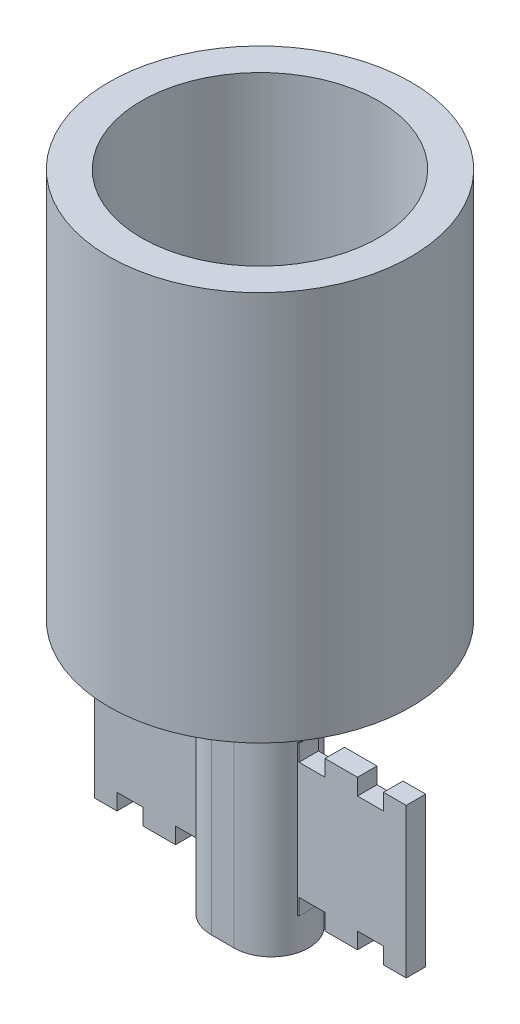
SolidWorks part; units mm, degrees
material "ABS"
ref_plane "Front Plane" through (0, 0, 0) normal (0, 0, 1) x (1, 0, 0)
ref_plane "Top Plane" through (0, 0, 0) normal (0, 1, 0) x (1, 0, 0)
ref_plane "Right Plane" through (0, 0, 0) normal (1, 0, 0) x (0, 0, -1)
sketch "Sketch1" plane through (0, 0, 0) normal (0, 1, 0) x (1, 0, 0)
  circle A0 centre (0, 0) radius 4.65
  dimension "D1" = 9.3
extrude "Boss-Extrude1" add sketch "Sketch1" along normal blind 1
sketch "Sketch2" plane through (0, 1, 0) normal (0, 1, 0) x (1, 0, 0)
  circle A0 centre (0, 0) radius 4.65 construction
  circle A1 centre (0, 0) radius 4.65
  circle A2 centre (0, 0) radius 3.65
  dimension "D1" = 1
extrude "Boss-Extrude2" add sketch "Sketch2" along normal blind 11
sketch "Sketch3" plane through (0, 0, 0) normal (0, -1, 0) x (1, 0, 0)
  line L0 (0.35, 0) -> (-0.35, 0) construction
  line L1 (0.35, -1.15) -> (-0.35, -1.15)
  line L2 (0.35, 1.15) -> (-0.35, 1.15)
  arc A0 (0.35, -1.15) -> (0.35, 1.15) centre (0.35, 0) ccw
  arc A1 (-0.35, 1.15) -> (-0.35, -1.15) centre (-0.35, 0) ccw
  point P2 (0, 0)
  point P8 (-1.5, 0)
  point P9 (1.5, 0)
  dimension "D1" = 1.15
  dimension "D2" = 3
extrude "Boss-Extrude3" add sketch "Sketch3" along normal blind 8
sketch "Sketch4" plane through (0, 0, 0) normal (0, 0, 1) x (1, 0, 0)
  line L0 (0.35, -8) -> (1.5, -8) construction
  line L1 (4.8, -2.4) -> (-4.8, -2.4)
  line L2 (4.8, -2.4) -> (4.8, -7)
  line L3 (4.8, -7) -> (-4.8, -7)
  line L4 (-4.8, -2.4) -> (-4.8, -7)
  line L5 (4.8, -2.4) -> (-4.8, -7) construction
  line L6 (4.8, -7) -> (-4.8, -2.4) construction
  point P0 (0, -4.7)
  dimension "D1" = 1
  dimension "D2" = 4.6
  dimension "D3" = 9.6
extrude "Boss-Extrude4" add sketch "Sketch4" along normal mid plane 0.6
sketch "Sketch5" plane through (0, 0, -0.3) normal (0, 0, -1) x (-1, 0, 0)
  line L0 (-4.8, -2.4) -> (-1.4602, -2.4) construction
  line L1 (-1.5, -2.4) -> (-2.3, -2.4)
  line L2 (-1.5, -2.4) -> (-1.5, -2.9)
  line L3 (-1.5, -2.9) -> (-2.3, -2.9)
  line L4 (-2.3, -2.4) -> (-2.3, -2.9)
  line L5 (-3.3, -2.4) -> (-4.1, -2.4)
  line L6 (-3.3, -2.4) -> (-3.3, -2.9)
  line L7 (-3.3, -2.9) -> (-4.1, -2.9)
  line L8 (-4.1, -2.4) -> (-4.1, -2.9)
  line L9 (0, 5.115) -> (0, -5.115) construction
  line L10 (4.1, -2.4) -> (4.1, -2.9)
  line L11 (3.3, -2.9) -> (4.1, -2.9)
  line L12 (3.3, -2.4) -> (3.3, -2.9)
  line L13 (3.3, -2.4) -> (4.1, -2.4)
  line L14 (2.3, -2.4) -> (2.3, -2.9)
  line L15 (1.5, -2.9) -> (2.3, -2.9)
  line L16 (1.5, -2.4) -> (1.5, -2.9)
  line L17 (1.5, -2.4) -> (2.3, -2.4)
  line L18 (-4.8, -4.7) -> (-1.4602, -4.7) construction
  line L19 (-4.8, -7) -> (-4.8, -2.4) construction
  line L20 (-1.4602, -2.4) -> (-1.4602, -7) construction
  line L21 (1.5, -7) -> (2.3, -7)
  line L22 (1.5, -7) -> (1.5, -6.5)
  line L23 (1.5, -6.5) -> (2.3, -6.5)
  line L24 (2.3, -7) -> (2.3, -6.5)
  line L25 (3.3, -7) -> (4.1, -7)
  line L26 (3.3, -7) -> (3.3, -6.5)
  line L27 (3.3, -6.5) -> (4.1, -6.5)
  line L28 (4.1, -7) -> (4.1, -6.5)
  line L29 (-4.1, -7) -> (-4.1, -6.5)
  line L30 (-3.3, -6.5) -> (-4.1, -6.5)
  line L31 (-3.3, -7) -> (-3.3, -6.5)
  line L32 (-3.3, -7) -> (-4.1, -7)
  line L33 (-2.3, -7) -> (-2.3, -6.5)
  line L34 (-1.5, -6.5) -> (-2.3, -6.5)
  line L35 (-1.5, -7) -> (-1.5, -6.5)
  line L36 (-1.5, -7) -> (-2.3, -7)
  dimension "D1" = 0.8
  dimension "D2" = 0.5
  dimension "D3" = 1
extrude "Cut-Extrude1" cut sketch "Sketch5" against normal through all
sketch "Sketch6" plane through (0, 0, 0) normal (0, -1, 0) x (1, 0, 0)
  line L0 (-0.75, 2) -> (-2.25, 2) construction
  line L1 (-0.75, 1.5) -> (-2.25, 1.5)
  line L2 (-0.75, 2.5) -> (-2.25, 2.5)
  line L3 (0, 0.0632) -> (0, -1.15) construction
  line L4 (-0.35, -1.15) -> (0.35, -1.15) construction
  line L5 (0.75, 2) -> (2.25, 2) construction
  line L6 (0.75, 1.5) -> (2.25, 1.5)
  line L7 (0.75, 2.5) -> (2.25, 2.5)
  arc A0 (-0.75, 1.5) -> (-0.75, 2.5) centre (-0.75, 2) ccw
  arc A1 (-2.25, 2.5) -> (-2.25, 1.5) centre (-2.25, 2) ccw
  arc A2 (0.75, 1.5) -> (0.75, 2.5) centre (0.75, 2) cw
  arc A3 (2.25, 2.5) -> (2.25, 1.5) centre (2.25, 2) cw
  point P2 (-1.5, 2)
  point P14 (1.5, 2)
  dimension "D1" = 1
  dimension "D2" = 1.5
  dimension "D3" = 1.5
  dimension "D4" = 1.5
extrude "Cut-Extrude2" cut sketch "Sketch6" against normal through all
